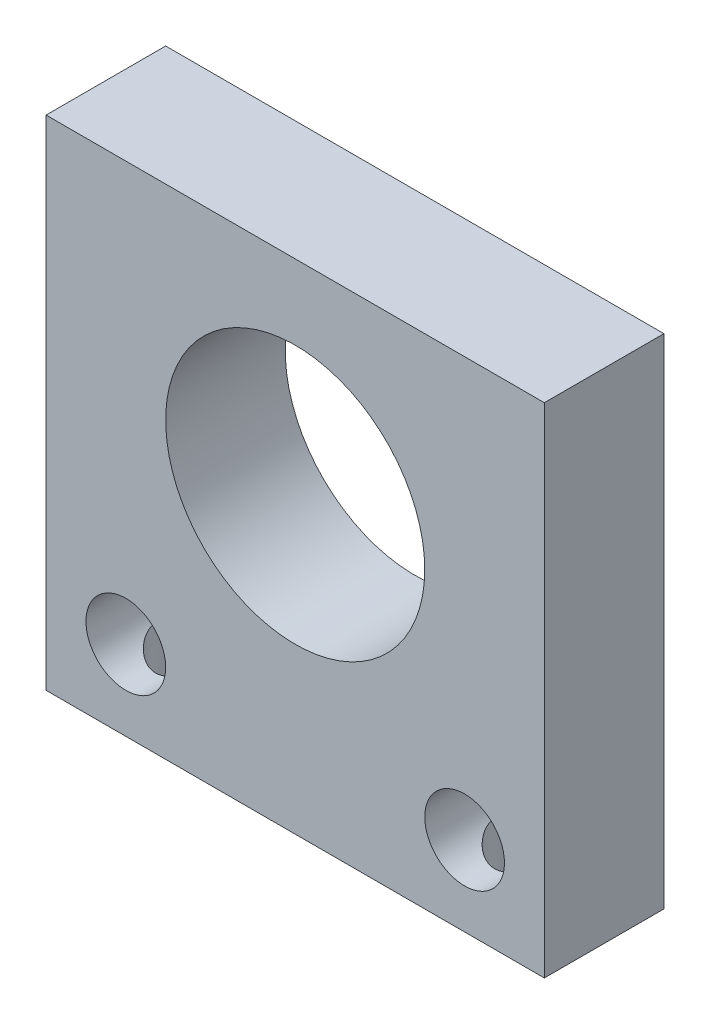
SolidWorks part; units mm, degrees
material "Beech"
ref_plane "Front Plane" through (0, 0, 0) normal (0, 0, 1) x (1, 0, 0)
ref_plane "Top Plane" through (0, 0, 0) normal (0, 1, 0) x (1, 0, 0)
ref_plane "Right Plane" through (0, 0, 0) normal (1, 0, 0) x (0, 0, -1)
sketch "Sketch1" plane through (0, 0, 0) normal (0, 0, 1) x (1, 0, 0)
  line L1 (-25, 25) -> (25, 25)
  line L2 (-25, 25) -> (-25, -25)
  line L3 (-25, -25) -> (25, -25)
  line L4 (25, 25) -> (25, -25)
  line L5 (-25, 25) -> (25, -25) construction
  line L6 (-25, -25) -> (25, 25) construction
  point P0 (0, 0)
  dimension "D1" = 50
  dimension "D2" = 50
extrude "Boss-Extrude1" add sketch "Sketch1" along normal blind 12
sketch "Sketch2" plane through (0, 0, 12) normal (0, 0, 1) x (1, 0, 0)
  line L3 (-25, -25) -> (25, -25) construction
  circle A0 centre (0, 4.5) radius 13
  dimension "D1" = 26
  dimension "D2" = 29.5
extrude "Cut-Extrude1" cut sketch "Sketch2" against normal up to next
sketch "Sketch3" plane through (0, 0, 12) normal (0, 0, 1) x (1, 0, 0)
  line L0 (-25, -25) -> (25, -25) construction
  line L1 (-25, 25) -> (-25, -25) construction
  line L2 (25, -25) -> (25, 25) construction
  circle A0 centre (-17, -17) radius 4
  circle A1 centre (17, -17) radius 4
  dimension "D1" = 8
  dimension "D2" = 8
  dimension "D5" = 8
  dimension "D6" = 8
  dimension "D3" = 8
  dimension "D4" = 8
extrude "Cut-Extrude2" cut sketch "Sketch3" against normal up to next
sketch "Sketch4" plane through (0, -25, 0) normal (0, -1, 0) x (1, 0, 0)
  line L0 (26.9668, 6) -> (-30.5117, 6) construction
  line L1 (25, 12) -> (25, 0) construction
  line L2 (-25, 12) -> (-25, 0) construction
  circle A0 centre (17, 6) radius 3
  circle A1 centre (-17, 6) radius 3
  dimension "D1" = 6
  dimension "D2" = 6
  dimension "D3" = 8
  dimension "D4" = 8
extrude "Cut-Extrude3" cut sketch "Sketch4" against normal up to next
